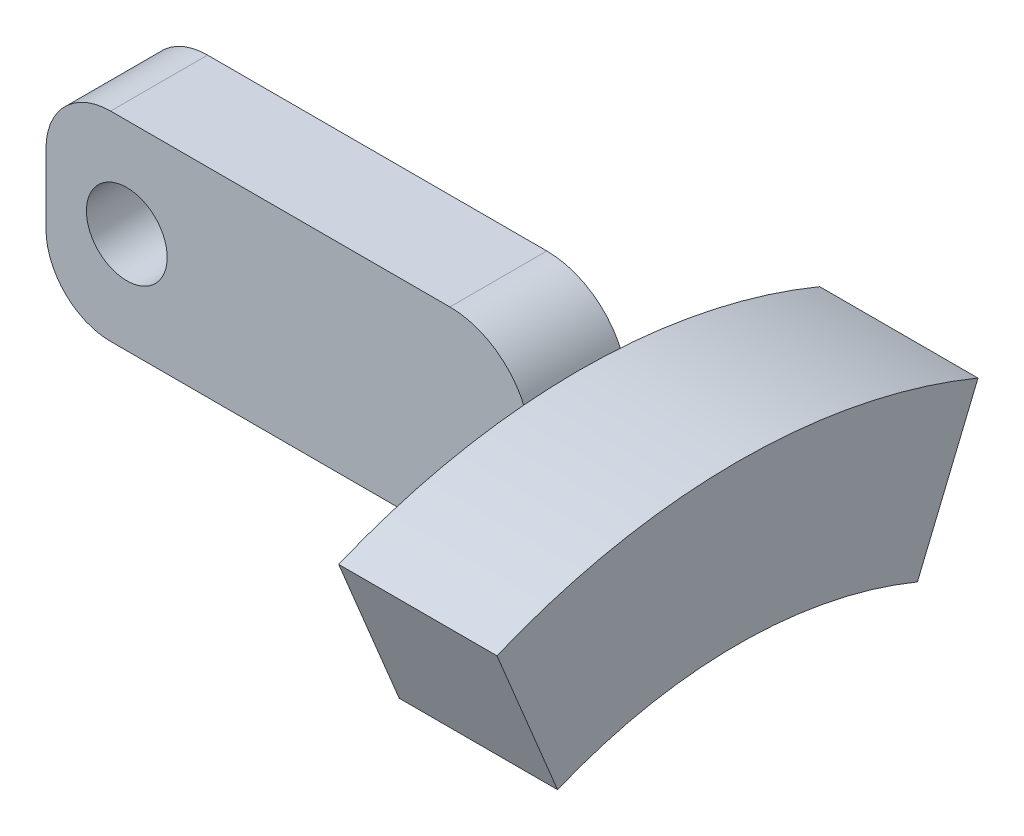
SolidWorks part; units mm, degrees
ref_plane "Спереди" through (0, 0, 0) normal (0, 0, 1) x (1, 0, 0)
ref_plane "Сверху" through (0, 0, 0) normal (0, 1, 0) x (1, 0, 0)
ref_plane "Справа" through (0, 0, 0) normal (1, 0, 0) x (0, 0, -1)
sketch "Эскиз1" plane through (0, 0, 0) normal (0, 0, 1) x (1, 0, 0)
  line L0 (50, 29) -> (40, 29) construction
  line L4 (40, 39) -> (40, 29) construction
  line L22 (49.9, 38.9) -> (40.1, 38.9)
  line L45 (50, 39) -> (50, 29) construction
  line L52 (50, 39) -> (40, 39) construction
  line L53 (66.4561, 0) -> (-18.0665, 0) construction
  line L54 (40.1, 38.9) -> (40.1, 29.1)
  line L55 (49.9, 29.1) -> (40.1, 29.1)
  line L56 (49.9, 38.9) -> (49.9, 29.1)
  dimension "D1" = 0.1
revolve "Повернуть1" add sketch "Эскиз1" angle 45 mid plane about L53
sketch "Эскиз2" plane through (40.1, 0, 0) normal (-1, 0, 0) x (0, 0, 1)
  line L0 (0, 46.709) -> (0, 25.7791) construction
  line L1 (-3, 41.2944) -> (-3, 28.9449)
  line L2 (3, 41.2944) -> (3, 28.9449)
  line L3 (-3, 41.2944) -> (3, 41.2944)
  line L6 (-3, 46.709) -> (-3, 25.7791) construction
  line L7 (3, 46.709) -> (3, 25.7791) construction
  arc A8 (11.1361, 26.8849) -> (-11.1361, 26.8849) centre (0, 0) ccw construction
  arc A9 (3, 28.9449) -> (-3, 28.9449) centre (0, 0) ccw
  dimension "D1" = 3
  dimension "D2" = 3
extrude "Бобышка-Вытянуть1" add sketch "Эскиз2" along normal blind 30 separate body
sketch "Эскиз4" plane through (0, 0, 0) normal (0, 0, 1) x (1, 0, 0)
  line L0 (10.1, 41.2944) -> (10.1, 29.1) construction
  line L1 (10.1, 35.1972) -> (15.1, 35.1972) construction
  line L2 (40.1, 35.9389) -> (40.1, 26.8849) construction
  circle A0 centre (15.1, 35.1972) radius 2.5
  point P8 (0, 0)
  point P9 (0, 0)
  point P12 (0, 0)
  point P13 (10.1, 30.1026)
  point P16 (10.1, 29.7544)
  dimension "D1" = 5
  dimension "D2" = 25
extrude "Вырез-Вытянуть1" cut sketch "Эскиз4" against normal mid plane 50
fillet "Скругление5" radius 4 2 edges at (10.1, 29.1, 0) (10.1, 41.2944, 0)
fillet "Скругление6" radius 5 1 edges at (40.1, 41.2944, 0)
